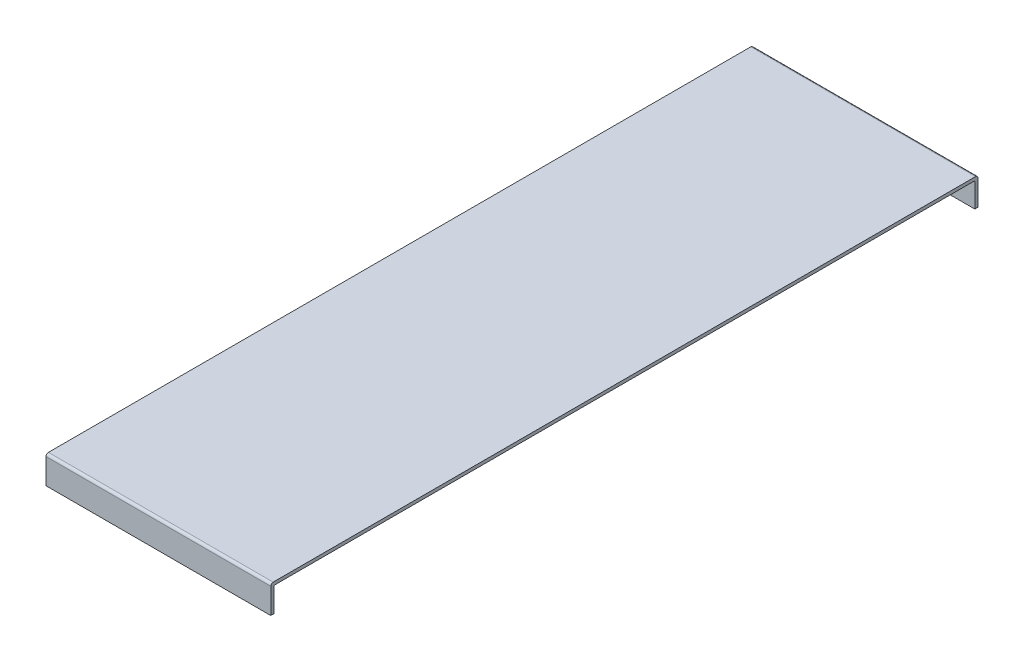
SolidWorks part; units mm, degrees
ref_plane "Front Plane" through (0, 0, 0) normal (0, 0, 1) x (1, 0, 0)
ref_plane "Top Plane" through (0, 0, 0) normal (0, 1, 0) x (1, 0, 0)
ref_plane "Right Plane" through (0, 0, 0) normal (1, 0, 0) x (0, 0, -1)
sketch "Sketch1" plane through (0, 0, 0) normal (0, 1, 0) x (1, 0, 0)
  line L1 (-155.6312, -176.9743) -> (-295.3312, -176.9743)
  line L2 (-155.6312, -176.9743) -> (-155.6312, 262.6357)
  line L3 (-155.6312, 262.6357) -> (-295.3312, 262.6357)
  line L4 (-295.3312, -176.9743) -> (-295.3312, 262.6357)
  dimension "D1" = 439.61
  dimension "D2" = 139.7
extrude "Boss-Extrude1" add sketch "Sketch1" along normal blind 2
sketch "Sketch2" plane through (0, 0, 0) normal (0, -1, 0) x (1, 0, 0)
  line L0 (-295.3312, -262.6357) -> (-295.3312, 176.9743) construction
  line L1 (-155.6312, -262.6357) -> (-295.3312, -262.6357)
  line L2 (-155.6312, -262.6357) -> (-155.6312, -260.6357)
  line L3 (-155.6312, -260.6357) -> (-295.3312, -260.6357)
  line L4 (-295.3312, -262.6357) -> (-295.3312, -260.6357)
  line L5 (-155.6312, 176.9743) -> (-155.6312, -262.6357) construction
  line L6 (-295.3312, 176.9743) -> (-155.6312, 176.9743)
  line L7 (-295.3312, 176.9743) -> (-295.3312, 174.9743)
  line L8 (-295.3312, 174.9743) -> (-155.6312, 174.9743)
  line L9 (-155.6312, 176.9743) -> (-155.6312, 174.9743)
  dimension "D1" = 2
  dimension "D2" = 2
extrude "Boss-Extrude2" add sketch "Sketch2" along normal blind 15.24
fillet "Fillet1" radius 1.5 2 edges at (-225.4812, 2, 176.9743) (-225.4812, 2, -262.6357)
fillet "Fillet2" radius 0.5 2 edges at (-225.4812, 0, 174.9743) (-225.4812, 0, -260.6357)
